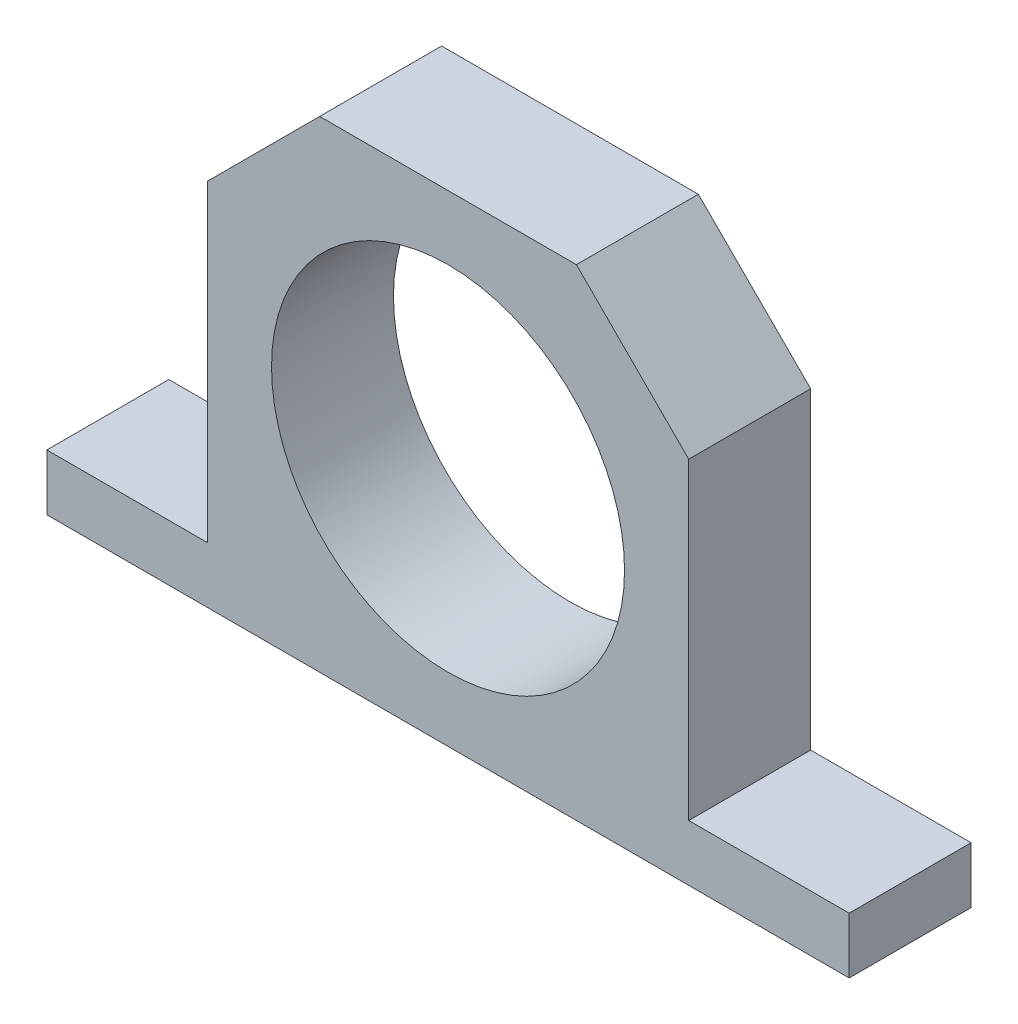
SolidWorks part; units mm, degrees
ref_plane "Front Plane" through (0, 0, 0) normal (0, 0, 1) x (1, 0, 0)
ref_plane "Top Plane" through (0, 0, 0) normal (0, 1, 0) x (1, 0, 0)
ref_plane "Right Plane" through (0, 0, 0) normal (1, 0, 0) x (0, 0, -1)
sketch "Sketch1" plane through (0, 0, 0) normal (0, 1, 0) x (1, 0, 0)
  line L1 (-15, 3.8) -> (15, 3.8)
  line L2 (-15, 3.8) -> (-15, -3.8)
  line L3 (-15, -3.8) -> (15, -3.8)
  line L4 (15, 3.8) -> (15, -3.8)
  line L5 (-15, 3.8) -> (15, -3.8) construction
  line L6 (-15, -3.8) -> (15, 3.8) construction
  point P0 (0, 0)
  dimension "D1" = 30
  dimension "D2" = 7.6
extrude "Boss-Extrude1" add sketch "Sketch1" along normal blind 30 contours L2 L1 L4 L3
sketch "Sketch2" plane through (0, 0, 3.8) normal (0, 0, 1) x (1, 0, 0)
  line L0 (-15, 23) -> (-8, 30)
  line L1 (-15, 30) -> (-15, 0) construction
  line L2 (-15, 30) -> (15, 30) construction
  line L3 (-8, 30) -> (-15, 30)
  line L4 (-15, 30) -> (-15, 23)
  line L5 (8, 30) -> (15, 30)
  line L6 (15, 30) -> (15, 23)
  line L7 (15, 30) -> (15, 0) construction
  line L8 (15, 23) -> (8, 30)
  circle A0 centre (0, 15) radius 11
  line M9 (15, 0) -> (15, 30)
  line M10 (15, 30) -> (-15, 30)
  line M11 (-15, 30) -> (-15, 0)
  dimension "D2" = 22
  dimension "D1" = 15
  dimension "D3" = 7
  dimension "D4" = 7
  dimension "D5" = 7
  dimension "D6" = 7
extrude "Cut-Extrude1" cut sketch "Sketch2" against normal blind 30 contours L0 M11 M10 | L8 M9 M10 | A0
sketch "Sketch3" plane through (0, 0, 0) normal (0, -1, 0) x (1, 0, 0)
  line L0 (-15, 3.8) -> (15, 3.8) construction
  line L1 (-25, 3.8) -> (25, 3.8)
  line L2 (-25, 3.8) -> (-25, -3.8)
  line L3 (-25, -3.8) -> (25, -3.8)
  line L4 (25, 3.8) -> (25, -3.8)
  line L5 (-15, -3.8) -> (15, -3.8) construction
  line L6 (-15, -3.8) -> (-15, 3.8) construction
  line L7 (15, -3.8) -> (15, 3.8) construction
  dimension "D1" = 10
  dimension "D2" = 10
extrude "Boss-Extrude2" add sketch "Sketch3" against normal blind 3.5 contours L2 L1 L4 L3
